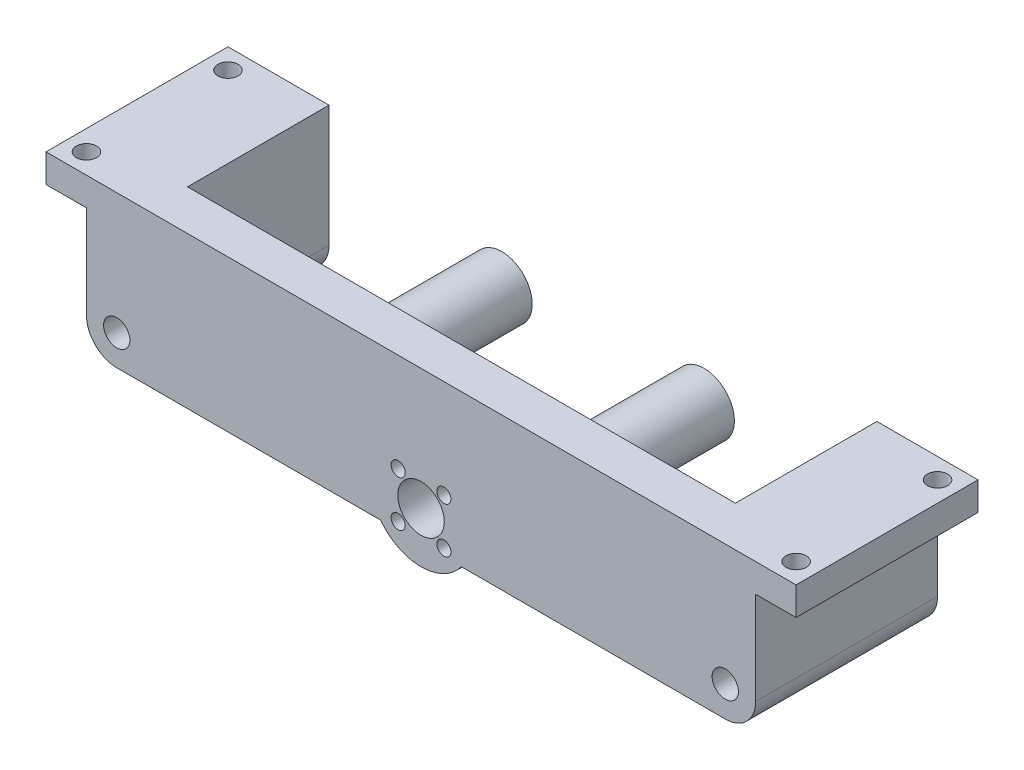
SolidWorks part; units mm, degrees
ref_plane "Front Plane" through (0, 0, 0) normal (0, 0, 1) x (1, 0, 0)
ref_plane "Top Plane" through (0, 0, 0) normal (0, 1, 0) x (1, 0, 0)
ref_plane "Right Plane" through (0, 0, 0) normal (1, 0, 0) x (0, 0, -1)
sketch "Sketch1" plane through (0, 0, 0) normal (0, 0, 1) x (1, 0, 0)
  line L0 (-12.5, 0) -> (-12.5, 30)
  line L1 (-5.6569, -5.6569) -> (5.6569, -5.6569) construction
  line L2 (-5.6569, -5.6569) -> (-5.6569, 5.6569) construction
  line L3 (-5.6569, 5.6569) -> (5.6569, 5.6569) construction
  line L4 (5.6569, -5.6569) -> (5.6569, 5.6569) construction
  line L5 (-5.6569, -5.6569) -> (5.6569, 5.6569) construction
  line L6 (-5.6569, 5.6569) -> (5.6569, -5.6569) construction
  line L7 (-12.5, 30) -> (12.5, 30)
  line L8 (12.5, 30) -> (12.5, 0)
  line L9 (-75.25, -7.5) -> (-10, -7.5)
  line L10 (-12.5, 30) -> (-82.75, 30)
  line L11 (-82.75, 30) -> (-82.75, 0)
  line L12 (0, 30) -> (0, 12.5) construction
  line L13 (12.5, 30) -> (82.75, 30)
  line L14 (75.25, -7.5) -> (10, -7.5)
  line L15 (82.75, 30) -> (82.75, 0)
  line L17 (-82.75, 30) -> (-92.75, 30)
  line L18 (-82.75, 30) -> (-82.75, 23)
  line L19 (-82.75, 23) -> (-92.75, 23)
  line L20 (-92.75, 30) -> (-92.75, 23)
  line L21 (82.75, 30) -> (92.75, 30)
  line L22 (82.75, 30) -> (82.75, 23)
  line L23 (82.75, 23) -> (92.75, 23)
  line L24 (92.75, 30) -> (92.75, 23)
  circle A0 centre (0, 0) radius 5.75
  circle A1 centre (0, 0) radius 12.5
  circle A2 centre (-5.6569, 5.6569) radius 1.75
  circle A3 centre (5.6569, 5.6569) radius 1.75
  circle A4 centre (5.6569, -5.6569) radius 1.75
  circle A5 centre (-5.6569, -5.6569) radius 1.75
  circle A6 centre (-75.25, 0) radius 3.25
  circle A7 centre (-75.25, 0) radius 7.5
  circle A8 centre (75.25, 0) radius 7.5
  circle A9 centre (75.25, 0) radius 3.25
  dimension "D1" = 11.5
  dimension "D2" = 25
  dimension "D4" = 3.5
  dimension "D5" = 30
  dimension "D6" = 6.5
  dimension "D7" = 15
  dimension "D3" = 8
  dimension "D8" = 30
  dimension "D9" = 75.25
  dimension "D10" = 10
  dimension "D11" = 7
  dimension "D12" = 10
  dimension "D13" = 7
extrude "Boss-Extrude1" add sketch "Sketch1" along normal blind 10 contours A1 L8 L7 L0 | A1 A5 A4 A3 A2 A0 | A7 A6 | A8 A9 | L14 A8 L15 L13 L8 A1 | A7 L9 A1 L0 L10 L11 | L18 L17 L20 L19 | L22 L21 L24 L23
sketch "Sketch2" plane through (0, 0, 0) normal (0, 0, -1) x (-1, 0, 0)
  line L0 (-67.75, 0) -> (-67.75, 30)
  line L1 (-92.75, 30) -> (92.75, 30) construction
  line L2 (0, 30) -> (0, 5.75) construction
  line L3 (67.75, 0) -> (67.75, 30)
  line L4 (-75.25, -7.5) -> (-10, -7.5) construction
  circle A0 centre (-75.25, 0) radius 7.5
  circle A1 centre (-75.25, 0) radius 3.25
  circle A2 centre (0, 0) radius 5.75 construction
  circle A3 centre (75.25, 0) radius 3.25
  circle A4 centre (75.25, 0) radius 7.5
  circle A5 centre (-25, 12.5) radius 7.5
  circle A6 centre (25, 12.5) radius 7.5
  circle M4 centre (75.25, 0) radius 3.25
  line M5 (-82.75, 23) -> (-82.75, 0)
  arc M6 (-82.75, 0) -> (-75.25, -7.5) centre (-75.25, 0) ccw
  arc M10 (75.25, -7.5) -> (82.75, 0) centre (75.25, 0) ccw
  line M11 (82.75, 0) -> (82.75, 23)
  line M12 (92.75, 30) -> (-92.75, 30)
  circle M18 centre (-75.25, 0) radius 3.25
  dimension "D1" = 15
  dimension "D2" = 6.5
  dimension "D3" = 15
  dimension "D4" = 20
  dimension "D5" = 25
extrude "Boss-Extrude2" add sketch "Sketch2" along normal blind 35 contours A0 L0 M12 M5 | A0 M6 M18 | L3 A4 M11 M12 | A4 M10 M4 | A5 | A6
sketch "Sketch3" plane through (0, 30, 0) normal (0, 1, 0) x (1, 0, 0)
  line L0 (0, 0) -> (0, -10) construction
  line L1 (92.75, -10) -> (-92.75, -10) construction
  line L2 (-92.75, 35) -> (-67.75, 35) construction
  line L3 (-92.75, -10) -> (-92.75, 35) construction
  line L4 (67.75, 35) -> (92.75, 35) construction
  line L5 (92.75, -10) -> (92.75, 35) construction
  circle A0 centre (-87.75, 30) radius 2.5
  circle A1 centre (-87.75, -5) radius 2.5
  circle A2 centre (87.75, 30) radius 2.5
  circle A3 centre (87.75, -5) radius 2.5
  dimension "D1" = 5
  dimension "D3" = 5
  dimension "D6" = 5
  dimension "D7" = 5
  dimension "D2" = 5
  dimension "D4" = 5
  dimension "D5" = 5
  dimension "D8" = 5
  dimension "D9" = 5
extrude "Cut-Extrude1" cut sketch "Sketch3" against normal blind 35
